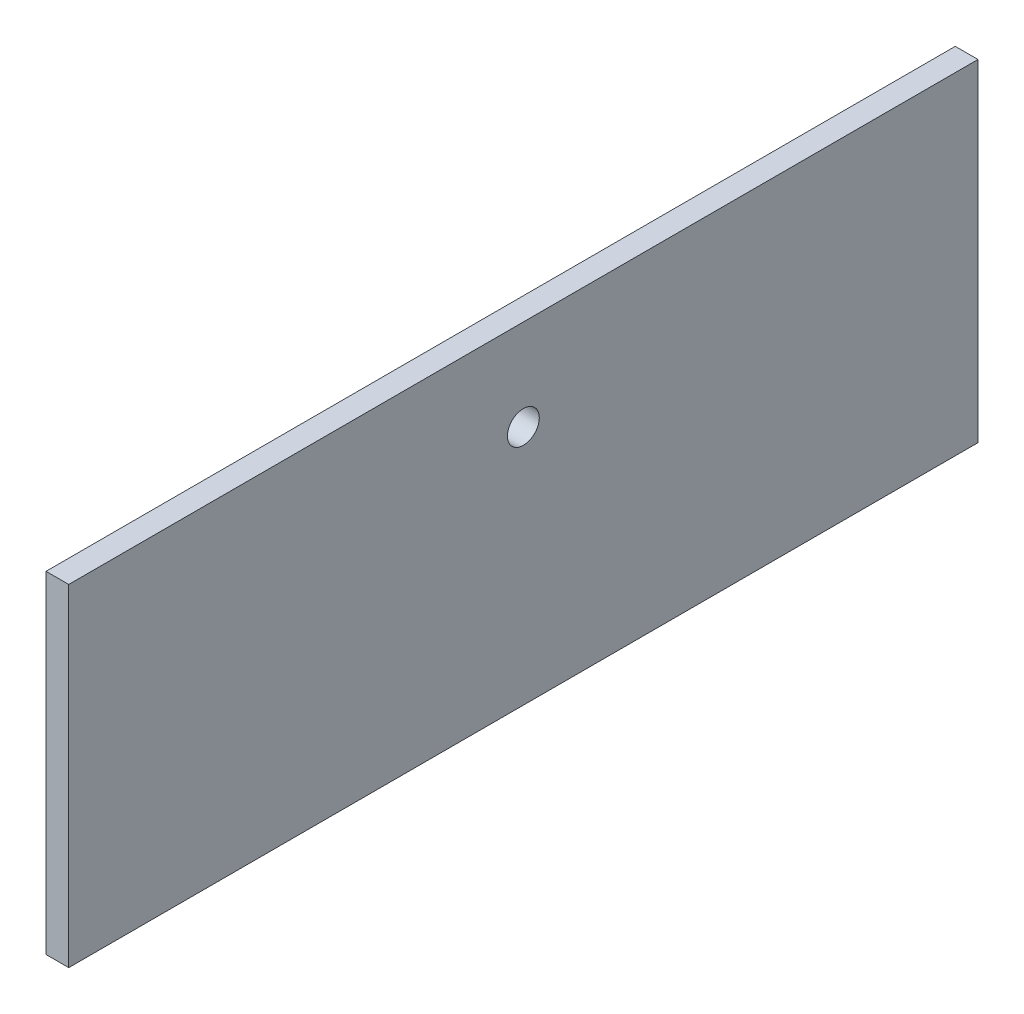
SolidWorks part; units mm, degrees
ref_plane "Front Plane" through (0, 0, 0) normal (0, 0, 1) x (1, 0, 0)
ref_plane "Top Plane" through (0, 0, 0) normal (0, 1, 0) x (1, 0, 0)
ref_plane "Right Plane" through (0, 0, 0) normal (1, 0, 0) x (0, 0, -1)
sketch "Sketch1" plane through (0, 0, 0) normal (0, 1, 0) x (1, 0, 0)
  line L1 (-75, 100) -> (75, 100)
  line L2 (-75, 100) -> (-75, -100)
  line L3 (-75, -100) -> (75, -100)
  line L4 (75, 100) -> (75, -100)
  line L5 (-75, 100) -> (75, -100) construction
  line L6 (-75, -100) -> (75, 100) construction
  point P0 (0, 0)
  dimension "D1" = 150
  dimension "D2" = 200
extrude "Boss-Extrude1" add sketch "Sketch1" along normal blind 100
shell "Shell2" thickness 5
sketch "Sketch5" plane through (0, 0, 0) normal (0, -1, 0) x (1, 0, 0)
  line L0 (-75, 100) -> (75, 100) construction
  circle A0 centre (-65, 91) radius 1.9
  circle A1 centre (-35, 91) radius 1.9
  circle A2 centre (-65, 67) radius 1.9
  circle A3 centre (-35, 67) radius 1.9
  dimension "D1" = 3.8
  dimension "D2" = 5
  dimension "D3" = 35
  dimension "D4" = 9
  dimension "D5" = 30
  dimension "D6" = 24
extrude "Cut-Extrude2" cut sketch "Sketch5" against normal blind 10
mirror "Mirror2" about plane through (0, 0, 0) normal (0, 0, 1) of "Cut-Extrude2"
sketch "Sketch6" plane through (0, 5, 0) normal (0, 1, 0) x (1, 0, 0)
  line L0 (-75, -100) -> (75, -100) construction
  line L1 (-70, 100) -> (-7.9429, 100) construction
  line L2 (-70, 100) -> (-70, -100) construction
  line L3 (-70, -100) -> (-7.9429, -100) construction
  line L4 (-7.9429, 100) -> (-7.9429, -100) construction
  line L10 (-70, -100) -> (-20, -100)
  line L11 (-70, -100) -> (-70, 100)
  line L12 (-70, 100) -> (-20, 100)
  line L13 (-20, -100) -> (-20, 100)
  dimension "D1" = 200
  dimension "D2" = 50
sketch "Sketch8" plane through (0, 0, 100) normal (0, 0, 1) x (1, 0, 0)
  line L3 (75, 17) -> (-15, 17)
  line L4 (-15, 0) -> (-15, 17)
  line L5 (75, 22) -> (-20, 22)
  line L6 (-20, 0) -> (-20, 22)
  line L8 (80, -5) -> (80, 22) construction
  line L9 (75, 0) -> (75, 17) construction
  line L10 (75, 0) -> (-15, 0) construction
  line L11 (80, -5) -> (-20, -5) construction
  line L12 (-15, 0) -> (-20, 0)
  line L13 (75, 17) -> (75, 22)
  line L14 (75, 100) -> (75, 0) construction
  line L15 (80, 22) -> (-20, 22) construction
  line L16 (-20, -5) -> (-20, 22) construction
  line L17 (-75, 0) -> (75, 0) construction
  line M3 (-75, 0) -> (75, 0)
  line M4 (75, 0) -> (75, 100)
  line M12 (70, 95) -> (70, 5)
  line M13 (70, 5) -> (-70, 5)
  dimension "D1" = 90
  dimension "D2" = 17
  dimension "D3" = 5
extrude "Boss-Extrude4" add sketch "Sketch8" against normal through all contours L6 L4 L3 L5 M13 M12 | L6 L4 M3 M13 | L5 L3 M4 M12
sketch "Sketch9" plane through (0, 0, 100) normal (0, 0, 1) x (1, 0, 0)
  line L1 (-15, 17) -> (86.1339, 17)
  line L2 (-15, 17) -> (-15, -14.9961)
  line L3 (-15, -14.9961) -> (86.1339, -14.9961)
  line L4 (86.1339, 17) -> (86.1339, -14.9961)
extrude "Cut-Extrude4" cut sketch "Sketch9" against normal through all
sketch "Sketch10" plane through (0, 17, 0) normal (0, -1, 0) x (1, 0, 0)
  line L0 (75, 100) -> (75, -100) construction
  circle A0 centre (60, 0) radius 4
  dimension "D1" = 8
  dimension "D2" = 15
extrude "Cut-Extrude5" cut sketch "Sketch10" against normal blind 10
sketch "Sketch11" plane through (0, 100, 0) normal (0, 1, 0) x (1, 0, 0)
  line L0 (-75, -100) -> (75, -100) construction
  line L1 (70, -95) -> (-70, -95)
  line L2 (70, -95) -> (70, -90)
  line L3 (70, -90) -> (-70, -90)
  line L4 (-70, -95) -> (-70, -90)
  line L5 (75, -100) -> (75, 100) construction
  line L6 (-75, 100) -> (-75, -100) construction
  point P6 (70, -92.5)
  dimension "D1" = 5
  dimension "D2" = 5
  dimension "D3" = 5
  dimension "D4" = 5
extrude "Cut-Extrude7" cut sketch "Sketch11" against normal up to surface (95 mm away) contours L4 L1 L2 L3 up to face at (-35, 5, -89.1)
mirror "Mirror3" about plane through (0, 0, 0) normal (0, 0, 1) of "Cut-Extrude7"
sketch "Sketch15" plane through (0, 100, 0) normal (0, 1, 0) x (1, 0, 0)
  circle A0 centre (50, 28) radius 1.2
  circle A1 centre (50, -28) radius 1.2
  circle A2 centre (-20, 20) radius 1.2
  circle A3 centre (-20, -20) radius 1.2
  dimension "D1" = 2.4
  dimension "D2" = 56
  dimension "D3" = 28
  dimension "D4" = 40
  dimension "D5" = 20
  dimension "D6" = 70
  dimension "D7" = 50
extrude "Cut-Extrude11" cut sketch "Sketch15" against normal blind 10
sketch "Sketch36" plane through (70, 0, 0) normal (-1, 0, 0) x (0, 0, 1)
  line L1 (-43.2021, 65) -> (16.7979, 65)
  line L2 (-43.2021, 65) -> (-43.2021, 60)
  line L3 (-43.2021, 60) -> (16.7979, 60)
  line L4 (16.7979, 65) -> (16.7979, 60)
  line L5 (-100, 0) -> (100, 0) construction
  point P6 (16.7979, 62.5)
  dimension "D1" = 65
  dimension "D2" = 5
  dimension "D3" = 16.7979
  dimension "D4" = 60
extrude "Boss-Extrude7" add sketch "Sketch36" along normal blind 10
mirror "Mirror5" about plane through (0, 0, 0) normal (1, 0, 0) of "Boss-Extrude7"
sketch "Sketch37" plane through (75, 0, 0) normal (1, 0, 0) x (0, 0, -1)
  circle A0 centre (0, 75) radius 3.5
  point P2 (0, 0)
  dimension "D1" = 7
  dimension "D2" = 75
extrude "Cut-Extrude15" cut sketch "Sketch37" against normal blind 60
sketch "Sketch38" plane through (-75, 0, 0) normal (-1, 0, 0) x (0, 0, 1)
  circle A0 centre (0, 80) radius 5
  point P2 (0, 0)
  dimension "D1" = 10
  dimension "D2" = 80
extrude "Cut-Extrude16" cut sketch "Sketch38" against normal blind 70
sketch "Sketch42" plane through (0, 0, 100) normal (0, 0, 1) x (1, 0, 0)
  line L0 (70, 22) -> (-20, 22) construction
  line L1 (70, 95) -> (-89.8409, 95)
  line L2 (70, 95) -> (70, 22)
  line L3 (70, 22) -> (-89.8409, 22)
  line L4 (-89.8409, 95) -> (-89.8409, 22)
  line L6 (-89.8409, 22) -> (106.3551, 22)
  line L7 (-89.8409, 22) -> (-89.8409, -3.7771)
  line L8 (-89.8409, -3.7771) -> (106.3551, -3.7771)
  line L9 (106.3551, 22) -> (106.3551, -3.7771)
  line L10 (-89.8409, 95) -> (99.534, 95)
  line L11 (-89.8409, 95) -> (-89.8409, 106.0783)
  line L12 (-89.8409, 106.0783) -> (99.534, 106.0783)
  line L13 (99.534, 95) -> (99.534, 106.0783)
extrude "Cut-Extrude20" cut sketch "Sketch42" against normal through all contours L2 L1 L4 L3 | L11 L10 L13 L12 | L7 L6 L9 L8
